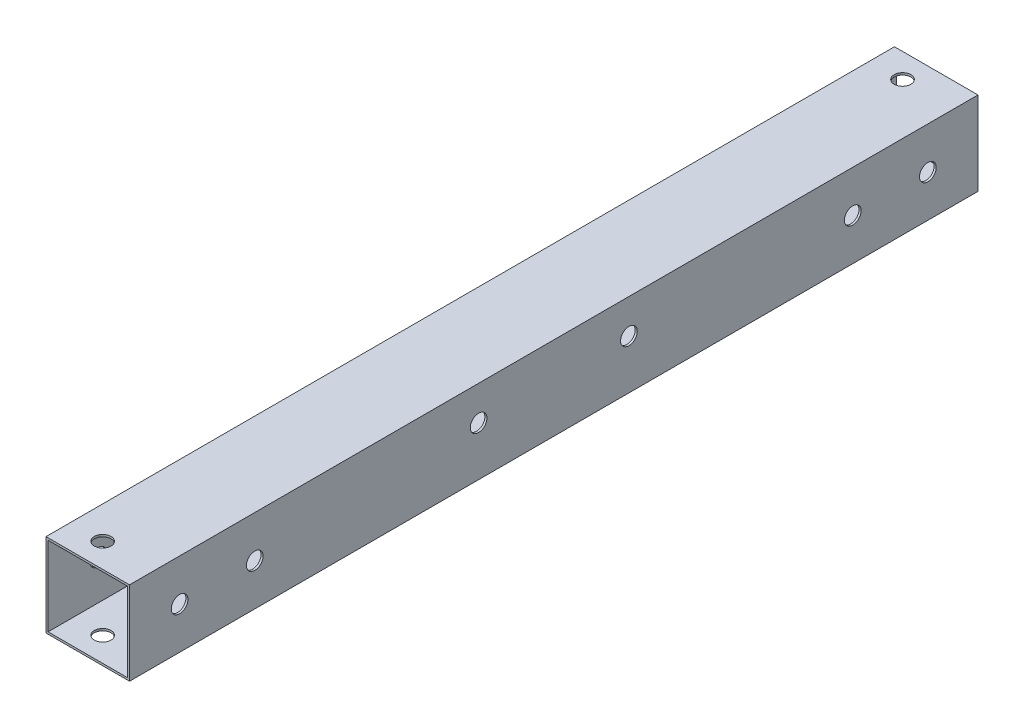
SolidWorks part; units mm, degrees
ref_plane "前视基准面" through (0, 0, 0) normal (0, 0, 1) x (1, 0, 0)
ref_plane "上视基准面" through (0, 0, 0) normal (0, 1, 0) x (1, 0, 0)
ref_plane "右视基准面" through (0, 0, 0) normal (1, 0, 0) x (0, 0, -1)
sketch "草图1" plane through (0, 0, 0) normal (0, 0, 1) x (1, 0, 0)
  line L1 (-10, 10) -> (10, 10)
  line L2 (-10, 10) -> (-10, -10)
  line L3 (-10, -10) -> (10, -10)
  line L4 (10, 10) -> (10, -10)
  line L5 (-10, 10) -> (10, -10) construction
  line L6 (-10, -10) -> (10, 10) construction
  line L7 (9.5, -9.5) -> (-9.5, -9.5)
  line L8 (9.5, -9.5) -> (9.5, 9.5)
  line L9 (9.5, 9.5) -> (-9.5, 9.5)
  line L10 (-9.5, -9.5) -> (-9.5, 9.5)
  line L11 (9.5, -9.5) -> (-9.5, 9.5) construction
  line L12 (9.5, 9.5) -> (-9.5, -9.5) construction
  point P0 (0, 0)
  point P5 (0, 0)
  dimension "D1" = 20
  dimension "D2" = 20
  dimension "D3" = 19
  dimension "D4" = 19
extrude "凸台-拉伸1" add sketch "草图1" against normal blind 203.2
sketch "草图2" plane through (-10, 0, 0) normal (-1, 0, 0) x (0, 0, 1)
  circle A4 centre (-30, 0) radius 2
  circle A5 centre (-83.6, 1.7949) radius 2
  circle A6 centre (-119.6, 1.7949) radius 2
  circle A7 centre (-173.2, 0) radius 2
  circle A9 centre (-191.2, 0) radius 2
  circle A11 centre (-12, 0) radius 2
extrude "切除-拉伸1" cut sketch "草图2" against normal through all
sketch "草图3" plane through (0, 10, 0) normal (0, 1, 0) x (1, 0, 0)
  circle A2 centre (-2.25, 197.3714) radius 2
  circle A3 centre (-2.25, 5.8286) radius 2
extrude "切除-拉伸2" cut sketch "草图3" against normal through all
